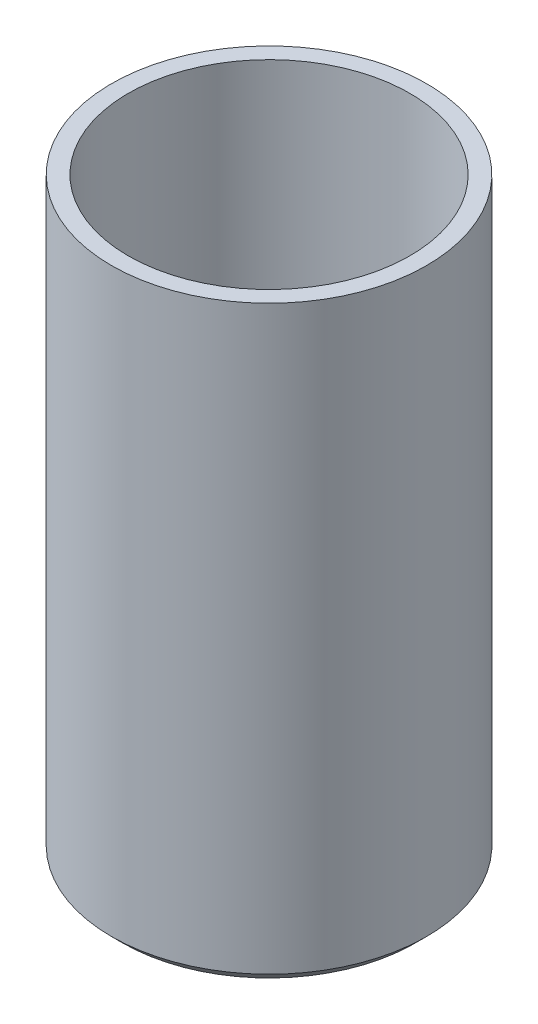
SolidWorks part; units mm, degrees
ref_plane "Front Plane" through (0, 0, 0) normal (0, 0, 1) x (1, 0, 0)
ref_plane "Top Plane" through (0, 0, 0) normal (0, 1, 0) x (1, 0, 0)
ref_plane "Right Plane" through (0, 0, 0) normal (1, 0, 0) x (0, 0, -1)
sketch "Sketch1" plane through (0, 0, 0) normal (0, 1, 0) x (1, 0, 0)
  circle A0 centre (0, 0) radius 14.1
  dimension "D1" = 28.2
extrude "Boss-Extrude1" add sketch "Sketch1" along normal blind 3
sketch "Sketch2" plane through (0, 3, 0) normal (0, 1, 0) x (1, 0, 0)
  circle A0 centre (0, 0) radius 14.1
  circle A1 centre (0, 0) radius 12.6
  dimension "D1" = 1.5
extrude "Boss-Extrude2" add sketch "Sketch2" along normal blind 50
chamfer "Chamfer1" distance 1 angle 45 1 edges at (0, 0, 14.1)
